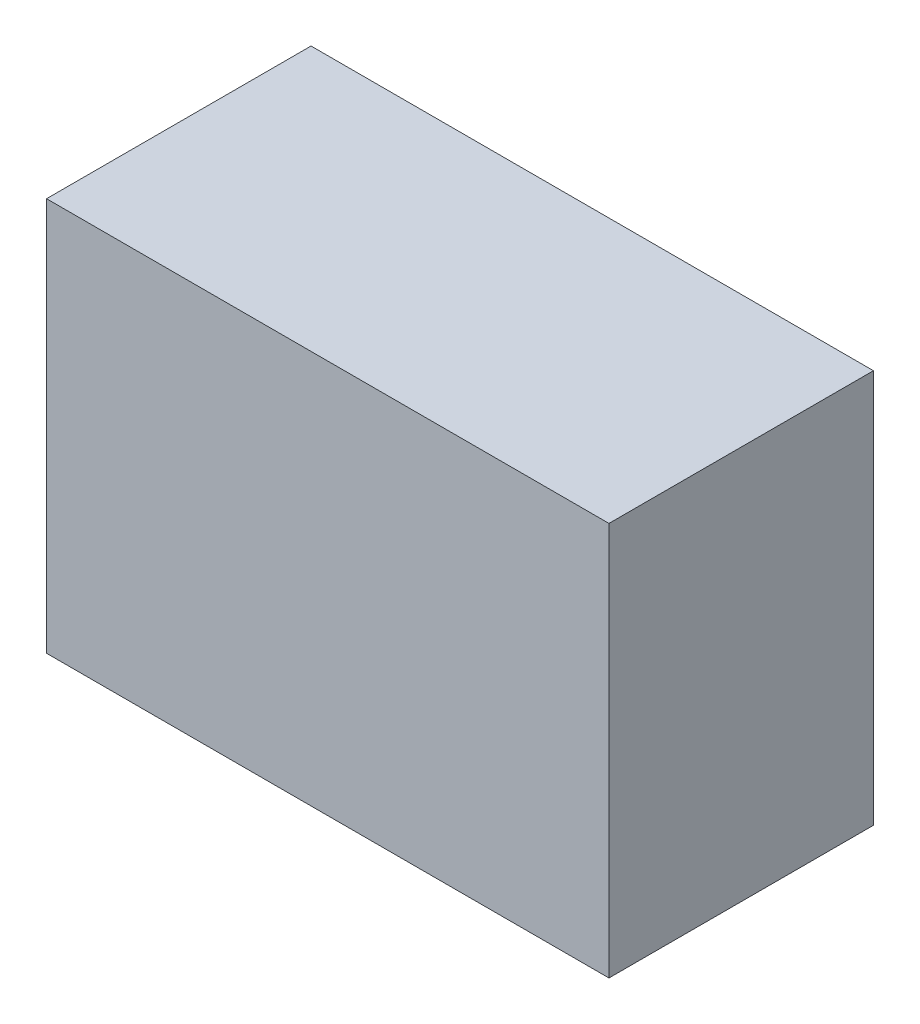
SolidWorks part; units mm, degrees
ref_plane "Front Plane" through (0, 0, 0) normal (0, 0, 1) x (1, 0, 0)
ref_plane "Top Plane" through (0, 0, 0) normal (0, 1, 0) x (1, 0, 0)
ref_plane "Right Plane" through (0, 0, 0) normal (1, 0, 0) x (0, 0, -1)
sketch "Sketch1" plane through (0, 0, 0) normal (0, 0, 1) x (1, 0, 0)
  line L1 (0, 0) -> (-100, 0)
  line L2 (0, 0) -> (0, 70)
  line L3 (0, 70) -> (-100, 70)
  line L4 (-100, 0) -> (-100, 70)
  dimension "D1" = 100
  dimension "D2" = 70
extrude "Boss-Extrude1" add sketch "Sketch1" along normal blind 47.0258
